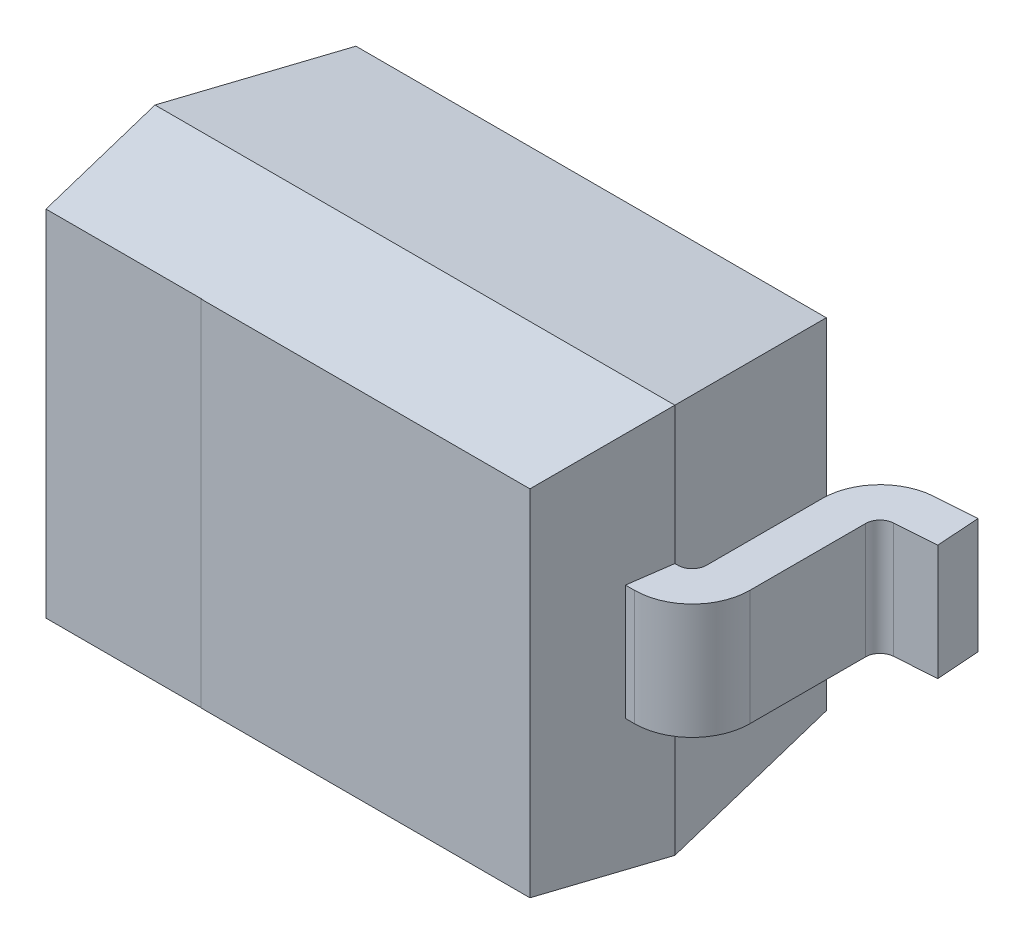
SolidWorks part; units mm, degrees
ref_plane "Top Plane" through (0, 0, 0) normal (0, 0, 1) x (1, 0, 0)
ref_plane "Front Plane" through (0, 0, 0) normal (0, 1, 0) x (1, 0, 0)
ref_plane "Right Plane" through (0, 0, 0) normal (1, 0, 0) x (0, 0, -1)
sketch "Sketch2" plane through (0, 0, 0) normal (0, 1, 0) x (1, 0, 0)
  line L0 (-0.8143, -0.05) -> (-0.9, -0.66)
  line L1 (-0.9, -0.66) -> (-0.8382, -1.1)
  line L2 (-0.8382, -1.1) -> (0.8382, -1.1)
  line L3 (0.8382, -1.1) -> (0.9, -0.66)
  line L4 (0.9, -0.66) -> (0.8143, -0.05)
  line L5 (0.8143, -0.05) -> (-0.8143, -0.05)
  line L6 (0.9, -0.66) -> (-0.9, -0.66) construction
  line L7 (0, -1.1) -> (0, -0.05) construction
  line L9 (0, -0.605) -> (0, 0.605) construction
  line L10 (-0.99, 0) -> (0.99, 0) construction
  dimension "D1" = 0.44
  dimension "D2" = 1.1
  dimension "D3" = 1.8
  dimension "D4" = 82
  dimension "D5" = 82
  dimension "D6" = 0.05
sketch "Sketch3" plane through (0, 0, 0) normal (0, 1, 0) x (1, 0, 0)
  line L0 (-0.8789, -0.81) -> (-0.9, -0.66)
  line L1 (-0.9, -0.66) -> (-0.91, -0.66)
  line L2 (-0.96, -0.61) -> (-0.96, -0.2095)
  line L3 (-1.146, -0.01) -> (-1.2895, 0)
  line L4 (-1.2895, 0) -> (-1.3, -0.1496)
  line L5 (-1.3, -0.1496) -> (-1.1565, -0.1597)
  line L6 (-1.11, -0.2095) -> (-1.11, -0.61)
  line L7 (-0.91, -0.81) -> (-0.8789, -0.81)
  line L9 (-0.99, 0) -> (0.99, 0) construction
  line L10 (-0.91, -0.66) -> (-0.91, -0.81) construction
  line L12 (0, 0) -> (0, -1.1) construction
  line L13 (-0.9, -0.66) -> (-0.8382, -1.1) construction
  arc A0 (-1.11, -0.61) -> (-0.91, -0.81) centre (-0.91, -0.61) ccw
  arc A1 (-0.91, -0.66) -> (-0.96, -0.61) centre (-0.91, -0.61) cw
  arc A2 (-0.96, -0.2095) -> (-1.146, -0.01) centre (-1.16, -0.2095) ccw
  arc A3 (-1.1565, -0.1597) -> (-1.11, -0.2095) centre (-1.16, -0.2095) cw
  dimension "D1" = 0.01
  dimension "D3" = 0.05
  dimension "D2" = 4
  dimension "LT" = 0.15
  dimension "LS" = 2.6
sketch "Sketch4" plane through (0, 0, 0) normal (1, 0, 0) x (0, 0, -1)
  line L0 (-0.05, -0.5893) -> (-0.66, -0.675)
  line L1 (-0.66, -0.675) -> (-1.1, -0.6132)
  line L2 (-1.1, -0.6132) -> (-1.1, 0.6132)
  line L3 (-1.1, 0.6132) -> (-0.66, 0.675)
  line L4 (-0.66, 0.675) -> (-0.05, 0.5893)
  line L5 (-0.05, 0.5893) -> (-0.05, -0.5893)
  line L6 (-0.66, 0.675) -> (-0.66, -0.675) construction
  line L7 (-1.1, 0) -> (-0.05, 0) construction
  line L9 (0.605, 0) -> (-0.605, 0) construction
  dimension "D1" = 82
  dimension "D2" = 82
  dimension "D3" = 1.35
extrude "Boss-Extrude1" add sketch "Sketch2" along normal mid plane 5
extrude "Cut-Extrude1" cut sketch "Sketch4" against normal through all and the other way through all flip side to cut
extrude "Boss-Extrude2" add sketch "Sketch3" along normal mid plane 0.4
mirror "Mirror1" about plane through (0, 0, 0) normal (1, 0, 0) of "Boss-Extrude2"
sketch "Sketch5" plane through (0, 0, 1.1) normal (0, 0, 1) x (1, 0, 0)
  line L0 (0.9, 0) -> (-0.9, 0) construction
  line L1 (-0.3, 0.675) -> (-0.9, 0.675)
  line L2 (-0.3, 0.675) -> (-0.3, -0.675)
  line L3 (-0.3, -0.675) -> (-0.9, -0.675)
  line L4 (-0.9, 0.675) -> (-0.9, -0.675)
  line L5 (-0.3, 0.675) -> (-0.9, -0.675) construction
  line L6 (-0.3, -0.675) -> (-0.9, 0.675) construction
  line L7 (0, -0.605) -> (0, 0.605) construction
  point P0 (-0.6, 0)
  dimension "D1" = 0.3
extrude "Cut-Extrude2" cut sketch "Sketch5" against normal blind 0.001
